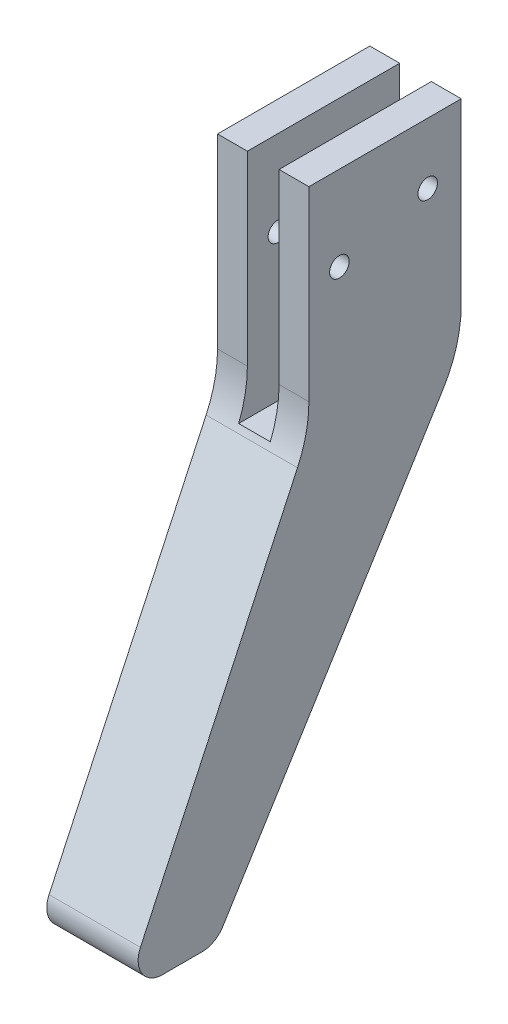
SolidWorks part; units mm, degrees
ref_plane "Front Plane" through (0, 0, 0) normal (0, 0, 1) x (1, 0, 0)
ref_plane "Top Plane" through (0, 0, 0) normal (0, 1, 0) x (1, 0, 0)
ref_plane "Right Plane" through (0, 0, 0) normal (1, 0, 0) x (0, 0, -1)
sketch "Sketch1" plane through (0, 0, 0) normal (1, 0, 0) x (0, 0, -1)
  line L0 (-9.8039, 21.5882) -> (15.1961, 21.5882)
  line L1 (15.1961, 21.5882) -> (15.1961, -13.4118)
  line L2 (15.1961, -13.4118) -> (-25.1139, -78.4118)
  line L3 (-25.1139, -78.4118) -> (-40.1139, -78.4118)
  line L4 (-40.1139, -78.4118) -> (-9.8039, -13.4118)
  line L5 (-9.8039, -13.4118) -> (-9.8039, 21.5882)
  dimension "D1" = 25
  dimension "D2" = 35
  dimension "D3" = 35
  dimension "D4" = 155
  dimension "D5" = 100
  dimension "D6" = 15
extrude "Boss-Extrude1" add sketch "Sketch1" along normal mid plane 15
fillet "Fillet1" radius 20 2 edges at (0, -13.4118, -15.1961) (0, -13.4118, 9.8039)
fillet "Fillet2" radius 4 2 edges at (0, -78.4118, 40.1139) (0, -78.4118, 25.1139)
sketch "Sketch2" plane through (0, 21.5882, 0) normal (0, 1, 0) x (1, 0, 0)
  line L0 (0, 0) -> (0, 24.3373) construction
  line L1 (-2.6, 19.226) -> (2.6, 19.226)
  line L2 (-2.6, 19.226) -> (-2.6, -16.9686)
  line L3 (-2.6, -16.9686) -> (2.6, -16.9686)
  line L4 (2.6, 19.226) -> (2.6, -16.9686)
  dimension "D1" = 2.6
  dimension "D2" = 5.2
extrude "Cut-Extrude1" cut sketch "Sketch2" against normal blind 38
sketch "Sketch3" plane through (-7.5, 0, 0) normal (-1, 0, 0) x (0, 0, 1)
  line L0 (-2.6961, 21.5882) -> (-2.6961, -33.5681) construction
  line L2 (-15.1961, 21.5882) -> (9.8039, 21.5882) construction
  line L3 (23.9407, -76.5199) -> (-12.193, -18.2543) construction
  line L4 (-9.6961, 11.5882) -> (4.8039, 7.703) construction
  line L5 (9.8039, 21.5882) -> (-15.1961, 21.5882) construction
  circle A0 centre (-9.6961, 11.5882) radius 1.6
  circle A1 centre (4.8039, 7.703) radius 1.6
  dimension "D1" = 3.2
  dimension "D2" = 3.2
  dimension "D3" = 15
  dimension "D4" = 7.5
  dimension "D5" = 7
  dimension "D6" = 10
extrude "Cut-Extrude2" cut sketch "Sketch3" against normal up to surface (15 mm away) up to face at (7.5, -31.7012, 11.1393)
